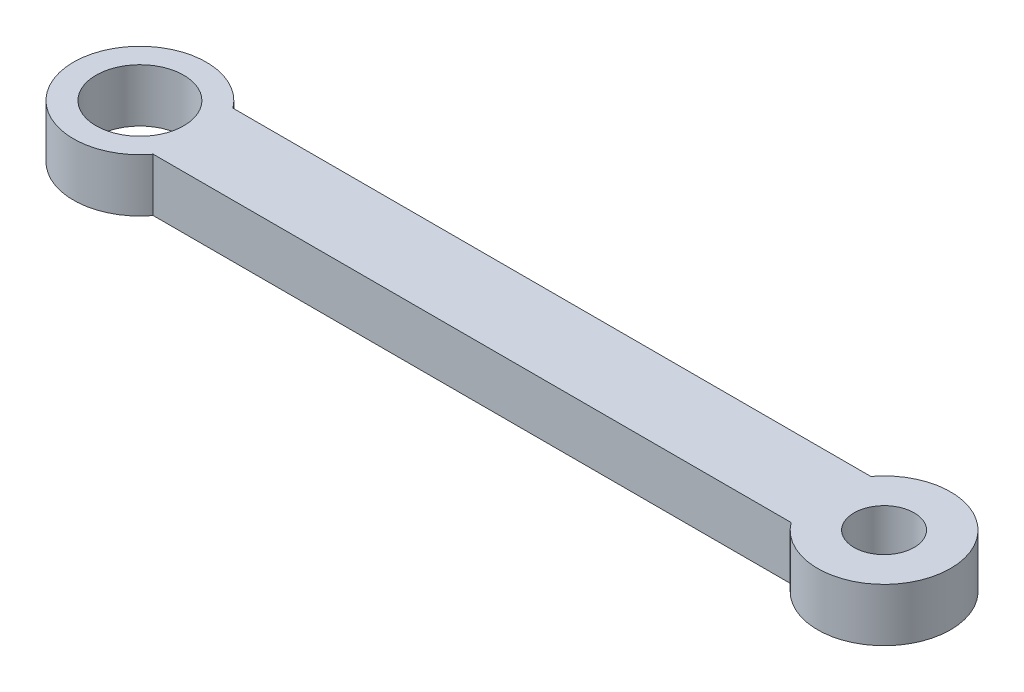
SolidWorks part; units mm, degrees
ref_plane "Front Plane" through (0, 0, 0) normal (0, 0, 1) x (1, 0, 0)
ref_plane "Top Plane" through (0, 0, 0) normal (0, 1, 0) x (1, 0, 0)
ref_plane "Right Plane" through (0, 0, 0) normal (1, 0, 0) x (0, 0, -1)
sketch "Sketch1" plane through (0, 0, 0) normal (0, 1, 0) x (1, 0, 0)
  line L0 (-12, 1.5) -> (12, 1.5)
  line L1 (-14, -1.5) -> (14, -1.5) construction
  line L2 (-14, -1.5) -> (-14, 1.5) construction
  line L3 (-14, 1.5) -> (14, 1.5) construction
  line L4 (14, -1.5) -> (14, 1.5) construction
  line L5 (-14, -1.5) -> (14, 1.5) construction
  line L6 (-14, 1.5) -> (14, -1.5) construction
  line L7 (-12, -1.5) -> (12, -1.5)
  circle A0 centre (-14, 0) radius 2.5 construction
  circle A1 centre (14, 0) radius 2.5 construction
  arc A2 (-12, 1.5) -> (-12, -1.5) centre (-14, 0) ccw
  arc A3 (12, 1.5) -> (12, -1.5) centre (14, 0) cw
  circle A4 centre (-14, 0) radius 1.65
  circle A5 centre (14, 0) radius 1.1303
  point P0 (0, 0)
  dimension "D3" = 5
  dimension "D4" = 3.3
  dimension "D5" = 2.2606
  dimension "D1" = 28
  dimension "D2" = 3
extrude "Boss-Extrude1" add sketch "Sketch1" along normal blind 2
